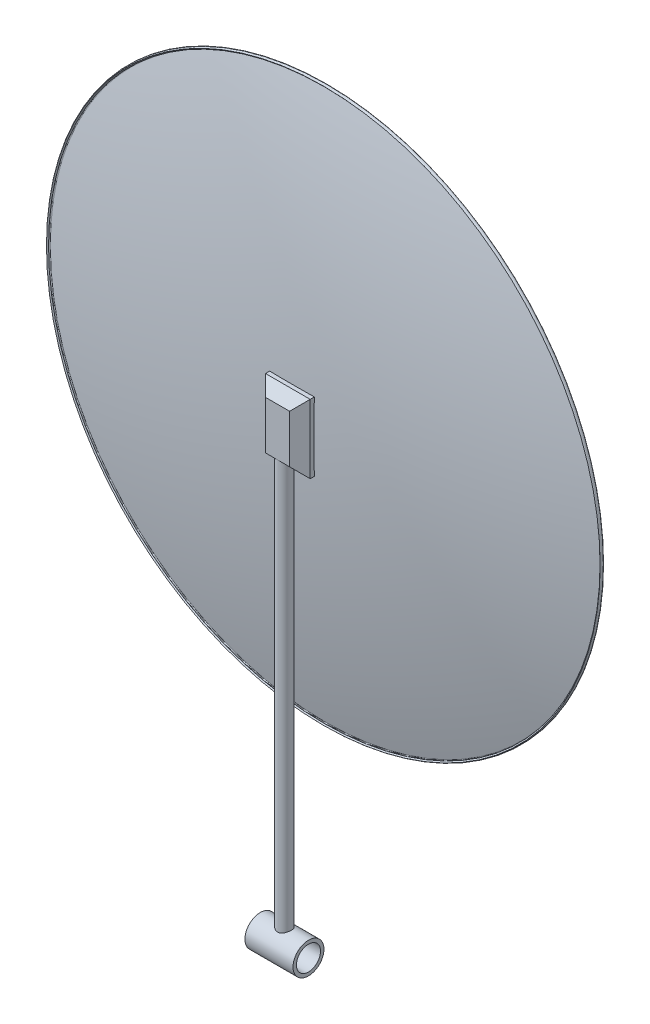
SolidWorks part; units mm, degrees
ref_plane "Front Plane" through (0, 0, 0) normal (0, 0, 1) x (1, 0, 0)
ref_plane "Top Plane" through (0, 0, 0) normal (0, 1, 0) x (1, 0, 0)
ref_plane "Right Plane" through (0, 0, 0) normal (1, 0, 0) x (0, 0, -1)
sketch "Sketch1" plane through (0, 0, 0) normal (1, 0, 0) x (0, 0, -1)
  line L0 (-1579.018, -401.0505) -> (-1580.4135, -402.6424)
  line L1 (-1625, 0) -> (-1627, 0)
  arc A0 (-1627, 0) -> (-1576.9385, -400.4923) centre (0, 0) ccw
  arc A1 (-1625, 0) -> (-1575, -400) centre (0, 0) ccw
  arc A2 (-1576.9385, -400.4923) -> (-1579.018, -401.0505) centre (-1577.982, -400.7573) cw
  arc A3 (-1407.2913, 812.5) -> (-1575, -400) centre (0, 0) ccw construction
  arc A4 (-1409.0233, 813.5) -> (-1576.9385, -400.4923) centre (0, 0) ccw construction
  arc A5 (-1575, -400) -> (-1580.4135, -402.6424) centre (-1577.982, -400.7573) cw
  point P1 (-193.0908, 0)
  point P3 (-552.7577, 0)
  dimension "D3" = 50
  dimension "D1" = 2
  dimension "D2" = 400
revolve "Revolve1" add sketch "Sketch1" angle 360 about L1
ref_plane "Düzlem1" through (0, 0, 1627) normal (0, 0, 1) x (1, 0, 0)
sketch "Çizim1" plane through (0, 0, 1627) normal (0, 0, 1) x (1, 0, 0)
  line L1 (-32.5, -50) -> (32.5, -50)
  line L2 (-32.5, -50) -> (-32.5, 50)
  line L3 (-32.5, 50) -> (32.5, 50)
  line L4 (32.5, -50) -> (32.5, 50)
  line L5 (-32.5, -50) -> (32.5, 50) construction
  line L6 (-32.5, 50) -> (32.5, -50) construction
  point P9 (0, 0)
  dimension "D4" = 100
  dimension "D5" = 65
extrude "Yükseklik-Ekstrüzyon1" add sketch "Çizim1" along normal blind 20 and the other way up to surface other way up to face at (-400, 0, 1575)
chamfer "Pah1" distance 15 angle 45 4 edges at (0, -50, 1647) (-32.5, 0, 1647) (0, 50, 1647) (32.5, 0, 1647)
sketch "Çizim4" plane through (0, 0, 0) normal (1, 0, 0) x (0, 0, -1)
  line L0 (-1632, 50) -> (-1632, -50) construction
  circle A0 centre (-1637, -650) radius 17.5
  circle A1 centre (-1637, -650) radius 22.5
  point P6 (-1632, 0)
  dimension "D1" = 35
  dimension "D2" = 45
  dimension "D3" = 10
  dimension "D4" = 650
extrude "Yükseklik-Ekstrüzyon2" add sketch "Çizim4" along normal mid plane 70 separate body
sketch "Çizim5" plane through (0, 0, 0) normal (1, 0, 0) x (0, 0, -1)
  line L0 (-1637, -627.5) -> (-1637, 0.0812)
  line L1 (-1637, -650) -> (-1690.8895, -650) construction
  circle A0 centre (-1637, -650) radius 22.5 construction
  point P4 (-1617.3225, -639.0891)
sweep "Süpür1" add path "Çizim5" circular profile diameter 20 parameters "D3"=20
sketch "Çizim14" plane through (0, -627.5, 0) normal (0, -1, 0) x (1, 0, 0)
  circle A1 centre (0, 1637) radius 10
  circle A2 centre (0, 1637) radius 10
  dimension "D1" = 0
extrude "Yükseklik-Ekstrüzyon3" add sketch "Çizim14" along normal up to surface (2.3444 mm away)
